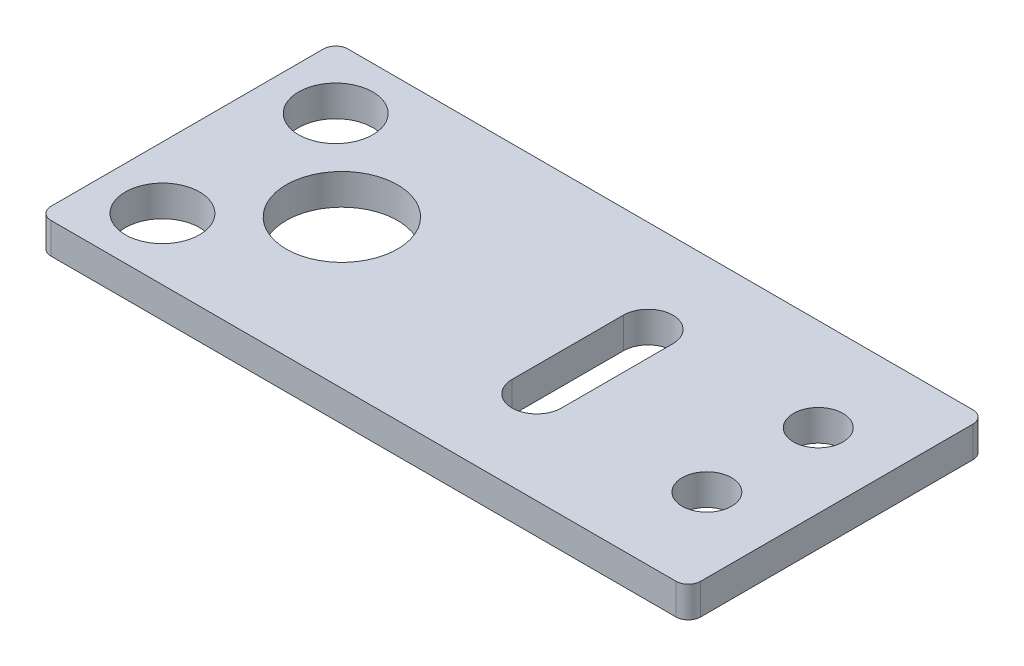
SolidWorks part; units mm, degrees
ref_plane "Front Plane" through (0, 0, 0) normal (0, 0, 1) x (1, 0, 0)
ref_plane "Top Plane" through (0, 0, 0) normal (0, 1, 0) x (1, 0, 0)
ref_plane "Right Plane" through (0, 0, 0) normal (1, 0, 0) x (0, 0, -1)
sketch "Sketch1" plane through (0, 0, 0) normal (0, 1, 0) x (1, 0, 0)
  line L0 (93, 0) -> (93, 48) construction
  line L1 (0, 0) -> (105, 0)
  line L2 (0, 0) -> (0, 48)
  line L3 (0, 48) -> (105, 48)
  line L5 (105, 48) -> (105, 0)
  line L6 (61.5, 33) -> (61.5, 15)
  line L8 (69.5, 33) -> (69.5, 15)
  circle A0 centre (10, 10) radius 6
  circle A1 centre (10, 38) radius 6
  circle A4 centre (25, 24) radius 9
  circle A6 centre (93, 15) radius 4
  circle A7 centre (93, 33) radius 4
  arc A8 (61.5, 15) -> (69.5, 15) centre (65.5, 15) ccw
  arc A10 (69.5, 33) -> (61.5, 33) centre (65.5, 33) ccw
  point P15 (0, 24)
  point P22 (93, 24)
  dimension "D1" = 12
  dimension "D9" = 18
  dimension "D13" = 8
  dimension "D14" = 8
  dimension "D16" = 8
  dimension "D2" = 10
  dimension "D5" = 12
  dimension "D3" = 10
  dimension "D4" = 10
  dimension "D6" = 28
  dimension "D8" = 15
  dimension "D11" = 9
  dimension "D12" = 18
  dimension "D15" = 27.5
  dimension "D17" = 105
extrude "Boss-Extrude1" add sketch "Sketch1" along normal blind 5
fillet "Fillet1" radius 2 4 edges at (0, 2.5, 0) (0, 2.5, -48) (105, 2.5, -48) (105, 2.5, 0)
